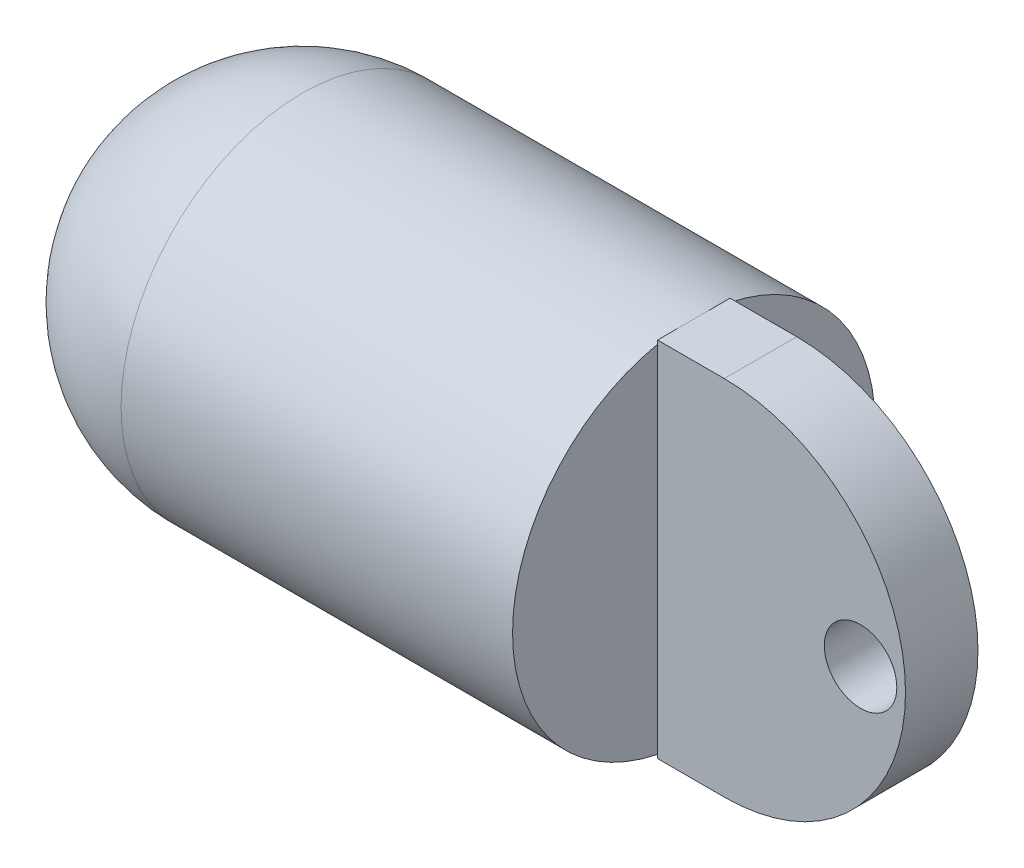
SolidWorks part; units mm, degrees
ref_plane "Front Plane" through (0, 0, 0) normal (0, 0, 1) x (1, 0, 0)
ref_plane "Top Plane" through (0, 0, 0) normal (0, 1, 0) x (1, 0, 0)
ref_plane "Right Plane" through (0, 0, 0) normal (1, 0, 0) x (0, 0, -1)
sketch "Sketch1" plane through (0, 0, 0) normal (1, 0, 0) x (0, 0, -1)
  circle A0 centre (0, 0) radius 12.5
  dimension "D1" = 25
extrude "Boss-Extrude1" add sketch "Sketch1" against normal blind 27
sketch "Sketch6" plane through (0, 0, 0) normal (1, 0, 0) x (0, 0, -1)
  line L0 (-2.5, 12.5) -> (-2.5, -12.5)
  line L1 (-2.5, 12.5) -> (2.5, 12.5)
  line L2 (-2.5, -12.5) -> (2.5, -12.5)
  line L3 (2.5, 12.5) -> (2.5, -12.5)
  line L4 (-2.5, 12.5) -> (2.5, -12.5) construction
  line L5 (-2.5, -12.5) -> (2.5, 12.5) construction
  point P1 (0, 0)
  dimension "D1" = 5
  dimension "D2" = 25
extrude "Boss-Extrude3" add sketch "Sketch6" along normal blind 4.6
sketch "Sketch8" plane through (0, 0, 2.5) normal (0, 0, 1) x (1, 0, 0)
  line L0 (4.6, 12.5) -> (4.6, -12.5) construction
  line L1 (4.6, 12.5) -> (4.6, -12.5)
  arc A0 (4.6, -12.5) -> (4.6, 12.5) centre (4.6, 0) ccw
extrude "Boss-Extrude4" add sketch "Sketch8" against normal blind 5
sketch "Sketch10" plane through (0, 0, 2.5) normal (0, 0, 1) x (1, 0, 0)
  line L0 (0, 12.2474) -> (0, -12.2474) construction
  line L1 (4.6, -12.5) -> (0, -12.5) construction
  circle A0 centre (14, 0) radius 2.5
  dimension "D1" = 5
  dimension "D2" = 14
  dimension "D3" = 12.5
extrude "Cut-Extrude1" cut sketch "Sketch10" against normal through all and the other way through all
sketch "Sketch11" plane through (-27, 0, 0) normal (-1, 0, 0) x (0, 0, 1)
  line L0 (0, 12.5) -> (0, -12.5)
  arc A0 (0, -12.5) -> (0, 12.5) centre (0, 0) ccw
revolve "Revolve1" add sketch "Sketch11" angle 180 about L0
